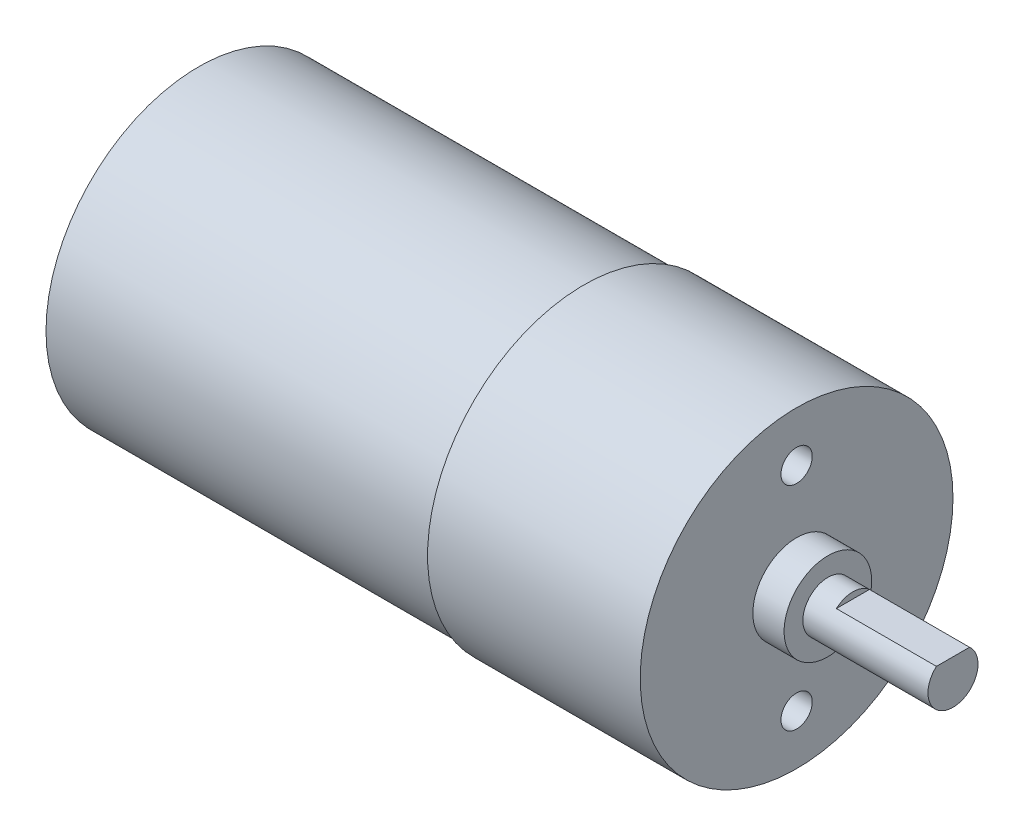
SolidWorks part; units mm, degrees
ref_plane "Front Plane" through (0, 0, 0) normal (0, 0, 1) x (1, 0, 0)
ref_plane "Top Plane" through (0, 0, 0) normal (0, 1, 0) x (1, 0, 0)
ref_plane "Right Plane" through (0, 0, 0) normal (1, 0, 0) x (0, 0, -1)
sketch "Sketch2" plane through (0, 0, 0) normal (1, 0, 0) x (0, 0, -1)
  circle A0 centre (0, 0) radius 12.5
  dimension "D1" = 25
extrude "Boss-Extrude1" add sketch "Sketch2" against normal blind 17
sketch "Sketch3" plane through (-17, 0, 0) normal (-1, 0, 0) x (0, 0, 1)
  circle A0 centre (0, 0) radius 12.2
  dimension "D1" = 24.4
extrude "Boss-Extrude2" add sketch "Sketch3" along normal blind 30.8
sketch "Sketch4" plane through (0, 0, 0) normal (1, 0, 0) x (0, 0, -1)
  circle A0 centre (0, 0) radius 3.5
  dimension "D1" = 7
extrude "Boss-Extrude3" add sketch "Sketch4" along normal blind 2.5
sketch "Sketch5" plane through (2.5, 0, 0) normal (1, 0, 0) x (0, 0, -1)
  circle A0 centre (0, 0) radius 2
  dimension "D1" = 4
extrude "Boss-Extrude4" add sketch "Sketch5" along normal blind 10
sketch "Sketch6" plane through (12.5, 0, 0) normal (1, 0, 0) x (0, 0, -1)
  line L0 (-1.3229, 1.5) -> (1.3229, 1.5)
  line L1 (0, 1.5) -> (0, 0) construction
  circle A0 centre (0, 0) radius 2 construction
  dimension "D1" = 1.5
extrude "Cut-Extrude1" cut sketch "Sketch6" against normal blind 8 and the other way through all
hole_wizard "M3 Tapped Hole1" positions "Sketch7" profile "Sketch8" tap size "M3" standard "ISO"
sketch "Sketch7" plane through (0, 0, 0) normal (1, 0, 0) x (0, 0, -1)
  line L0 (0, 8.5) -> (0, -8.5) construction
  point P0 (0, 8.5)
  point P2 (0, -8.5)
  dimension "D1" = 17
cosmetic thread "Hole Thread1" parameters "D1"=3.05, "D2"=3
cosmetic thread "Hole Thread2" parameters "D1"=3.05, "D2"=3
sketch "Sketch8" plane through (0, 8.5, 0) normal (0, 1, 0) x (0, 0, -1)
  line L0 (0, 0) -> (0, 5.3011)
  line L1 (0, 5.3011) -> (1.25, 4.55)
  line L2 (1.25, 4.55) -> (1.25, 0)
  line L5 (1.25, 0) -> (0, 0)
  line L10 (0, 5.3011) -> (-1.25, 4.55) construction
  line L11 (0, -6.35) -> (0, 107.95) construction
  dimension "Tap Drill Dia." = 2.5
  dimension "Tap Drill Depth" = 4.55
  dimension "Drill Angle" = 118
